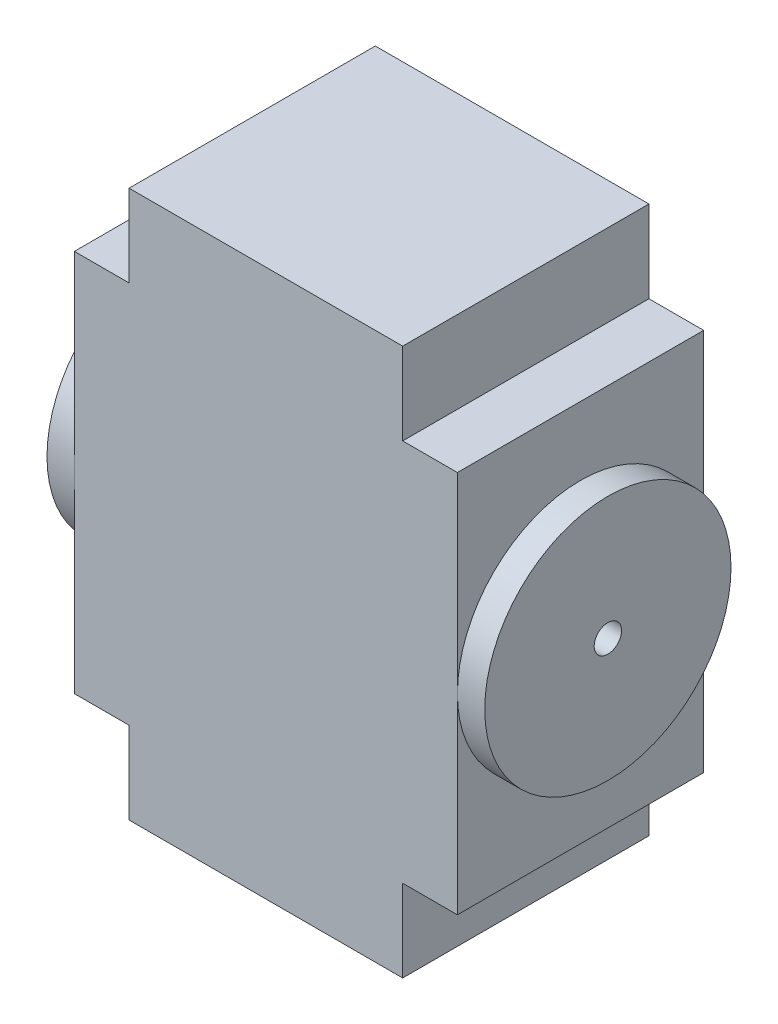
SolidWorks part; units mm, degrees
ref_plane "前视基准面" through (0, 0, 0) normal (0, 0, 1) x (1, 0, 0)
ref_plane "上视基准面" through (0, 0, 0) normal (0, 1, 0) x (1, 0, 0)
ref_plane "右视基准面" through (0, 0, 0) normal (1, 0, 0) x (0, 0, -1)
other "Configuration Table"
sketch "草图4" plane through (0, 0, 0) normal (0, 0, 1) x (1, 0, 0)
  line L1 (-2.5, -5) -> (2.5, -5)
  line L2 (-2.5, -5) -> (-2.5, 5)
  line L3 (-2.5, 5) -> (2.5, 5)
  line L4 (2.5, -5) -> (2.5, 5)
  line L5 (-2.5, -5) -> (2.5, 5) construction
  line L6 (-2.5, 5) -> (2.5, -5) construction
  point P0 (0, 0)
  dimension "D1" = 5
  dimension "D2" = 10
extrude "凸台-拉伸2" add sketch "草图4" along normal blind 4.5
sketch "草图5" plane through (2.5, 0, 0) normal (1, 0, 0) x (0, 0, -1)
  line L0 (0, -5) -> (0, 5) construction
  line L1 (-4.5, -3.5) -> (0, -3.5)
  line L2 (-4.5, -3.5) -> (-4.5, 3.5)
  line L3 (-4.5, 3.5) -> (0, 3.5)
  line L4 (0, -3.5) -> (0, 3.5)
  line L5 (-4.5, -3.5) -> (0, 3.5) construction
  line L6 (-4.5, 3.5) -> (0, -3.5) construction
  line L7 (-4.5, 5) -> (0, 5) construction
  point P0 (-2.25, 0)
  dimension "D1" = 7
  dimension "D2" = 4.5
  dimension "D3" = 1.5
extrude "凸台-拉伸3" add sketch "草图5" along normal blind 1
sketch "草图6" plane through (-2.5, 0, 0) normal (-1, 0, 0) x (0, 0, 1)
  line L0 (0, 5) -> (0, -5) construction
  line L1 (4.5, -3.5) -> (0, -3.5)
  line L2 (4.5, -3.5) -> (4.5, 3.5)
  line L3 (4.5, 3.5) -> (0, 3.5)
  line L4 (0, -3.5) -> (0, 3.5)
  line L5 (4.5, -3.5) -> (0, 3.5) construction
  line L6 (4.5, 3.5) -> (0, -3.5) construction
  line L7 (4.5, 5) -> (0, 5) construction
  point P0 (2.25, 0)
  dimension "D1" = 7
  dimension "D2" = 1.5
extrude "凸台-拉伸4" add sketch "草图6" along normal blind 1
sketch "草图7" plane through (3.5, 0, 0) normal (1, 0, 0) x (0, 0, -1)
  circle A0 centre (-2.25, 0) radius 2.25
extrude "凸台-拉伸5" add sketch "草图7" along normal blind 0.5
mirror "镜向1" about plane through (0, 0, 0) normal (1, 0, 0) of "凸台-拉伸5"
sketch "草图8" plane through (4, 0, 0) normal (1, 0, 0) x (0, 0, -1)
  circle A0 centre (-2.25, 0) radius 0.25
  dimension "D1" = 0.5
extrude "切除-拉伸1" cut sketch "草图8" against normal up to vertex (0.5 mm away)
sketch "草图9" plane through (-4, 0, 0) normal (-1, 0, 0) x (0, 0, 1)
  circle A0 centre (2.25, 0) radius 0.25
  dimension "D1" = 0.5
extrude "切除-拉伸2" cut sketch "草图9" against normal up to vertex (0.5 mm away)
